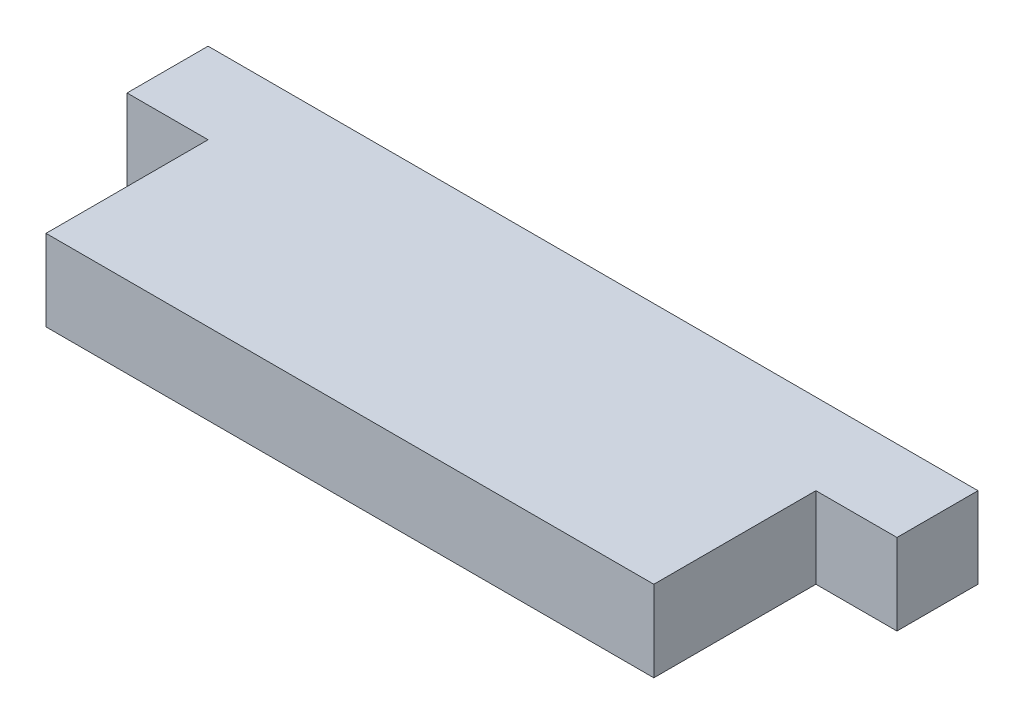
SolidWorks part; units mm, degrees
ref_plane "Front Plane" through (0, 0, 0) normal (0, 0, 1) x (1, 0, 0)
ref_plane "Top Plane" through (0, 0, 0) normal (0, 1, 0) x (1, 0, 0)
ref_plane "Right Plane" through (0, 0, 0) normal (1, 0, 0) x (0, 0, -1)
sketch "Sketch1" plane through (0, 0, 0) normal (0, 0, 1) x (1, 0, 0)
  line L1 (-7.5, 1) -> (7.5, 1)
  line L2 (-7.5, 1) -> (-7.5, -1)
  line L3 (-7.5, -1) -> (7.5, -1)
  line L4 (7.5, 1) -> (7.5, -1)
  dimension "D1" = 15
  dimension "D2" = 1
  dimension "D3" = 2
  dimension "D4" = 7.5
extrude "Boss-Extrude1" add sketch "Sketch1" along normal blind 4
sketch "Sketch2" plane through (0, 0, 0) normal (0, 0, -1) x (-1, 0, 0)
  line L0 (-7.5, 1) -> (7.5, 1) construction
  line L1 (-9.5, 1) -> (9.5, 1)
  line L2 (-9.5, 1) -> (-9.5, -1)
  line L3 (-9.5, -1) -> (9.5, -1)
  line L4 (9.5, 1) -> (9.5, -1)
  line L5 (7.5, -1) -> (-7.5, -1) construction
  line L6 (-7.5, -1) -> (-7.5, 1) construction
  line L7 (7.5, 1) -> (7.5, -1) construction
  dimension "D1" = 2
  dimension "D2" = 2
extrude "Boss-Extrude2" add sketch "Sketch2" along normal blind 2
